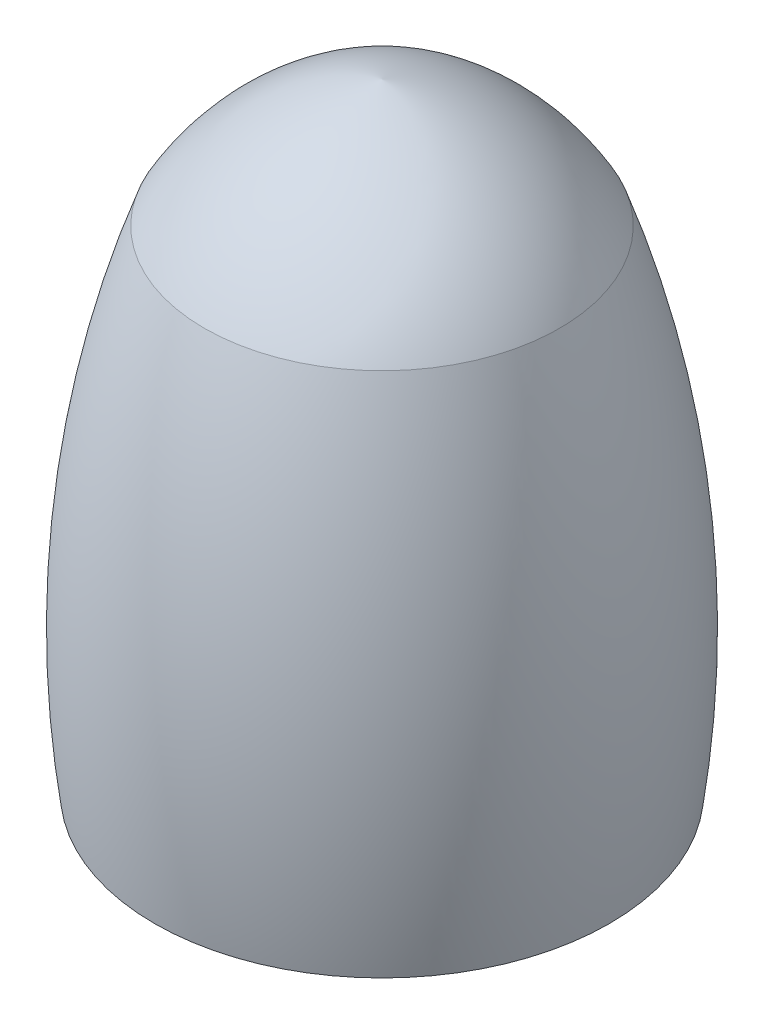
SolidWorks part; units mm, degrees
ref_plane "정면" through (0, 0, 0) normal (0, 0, 1) x (1, 0, 0)
ref_plane "윗면" through (0, 0, 0) normal (0, 1, 0) x (1, 0, 0)
ref_plane "우측면" through (0, 0, 0) normal (1, 0, 0) x (0, 0, -1)
sketch "스케치1" plane through (0, 0, 0) normal (1, 0, 0) x (0, 0, -1)
  line L0 (0, 0) -> (0.8203, 0)
  line L1 (0.8203, 0) -> (1.2805, -0.545)
  line L2 (1.2805, -0.545) -> (2.7805, -0.545)
  line L3 (0, 7) -> (0, 0) construction
  line L4 (0, 0) -> (0, 7)
  arc A0 (2.7805, -0.545) -> (2.1718, 5.4525) centre (-9.8861, 1.199) ccw
  arc A1 (2.1718, 5.4525) -> (0, 7) centre (-0.5794, 3.8891) ccw
  point P9 (2.9, 1.199)
  dimension "D1" = 5.8
  dimension "D2" = 7
  dimension "D3" = 1.5
revolve "회전1" add sketch "스케치1" angle 360 about L3
